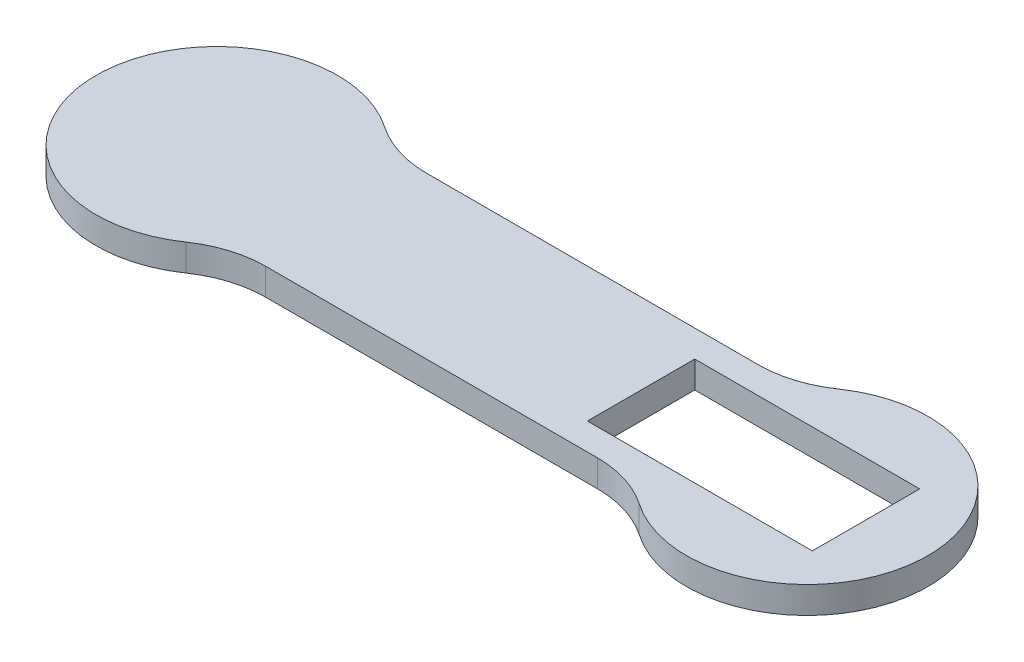
SolidWorks part; units mm, degrees
material "ABS"
ref_plane "Front Plane" through (0, 0, 0) normal (0, 0, 1) x (1, 0, 0)
ref_plane "Top Plane" through (0, 0, 0) normal (0, 1, 0) x (1, 0, 0)
ref_plane "Right Plane" through (0, 0, 0) normal (1, 0, 0) x (0, 0, -1)
other "Center of Mass"
sketch "Sketch2" plane through (0, 0, 0) normal (0, 1, 0) x (1, 0, 0)
  line L0 (0, 0) -> (136.4639, 0) construction
  line L1 (24.1091, 15) -> (85.8909, 15)
  line L3 (24.1091, -15) -> (85.8909, -15)
  line L5 (137.9207, 0) -> (181.8456, 0) construction
  arc A0 (12.7637, 18.5294) -> (12.7637, -18.5294) centre (0, 0) ccw
  arc A1 (97.2363, -18.5294) -> (97.2363, 18.5294) centre (110, 0) ccw
  arc A2 (97.2363, -18.5294) -> (85.8909, -15) centre (85.8909, -35) ccw
  arc A3 (97.2363, 18.5294) -> (85.8909, 15) centre (85.8909, 35) cw
  arc A4 (24.1091, -15) -> (12.7637, -18.5294) centre (24.1091, -35) ccw
  arc A5 (24.1091, 15) -> (12.7637, 18.5294) centre (24.1091, 35) cw
  point P16 (16.7705, -15)
  point P19 (16.7705, 15)
  dimension "D1" = 45
  dimension "D4" = 45
  dimension "D5" = 20
  dimension "D2" = 30
  dimension "D3" = 110
extrude "Boss-Extrude1" add sketch "Sketch2" along normal blind 5
sketch "Sketch3" plane through (0, 5, 0) normal (0, 1, 0) x (1, 0, 0)
  line L0 (0, 0) -> (125.1104, 0) construction
  line L1 (125.1104, 0) -> (159.77, 0) construction
  line L3 (73, -10) -> (127, -10)
  line L4 (73, -10) -> (73, 10)
  line L5 (73, 10) -> (127, 10)
  line L6 (127, -10) -> (127, 10)
  line L7 (73, -10) -> (127, 10) construction
  line L8 (73, 10) -> (127, -10) construction
  line L9 (79.05, -10.5) -> (120.95, -10.5)
  line L10 (79.05, -10.5) -> (79.05, 10.5)
  line L11 (79.05, 10.5) -> (120.95, 10.5)
  line L12 (120.95, -10.5) -> (120.95, 10.5)
  line L13 (79.05, -10.5) -> (120.95, 10.5) construction
  line L14 (79.05, 10.5) -> (120.95, -10.5) construction
  arc A0 (97.2363, -18.5294) -> (97.2363, 18.5294) centre (110, 0) ccw construction
  point P4 (100, 0)
  point P12 (100, 0)
  dimension "D2" = 17
  dimension "D1" = 20
  dimension "D3" = 54
  dimension "D4" = 41.9
  dimension "D5" = 21
extrude "Cut-Extrude1" cut sketch "Sketch3" against normal through all contours L3 L12 L5 L10
